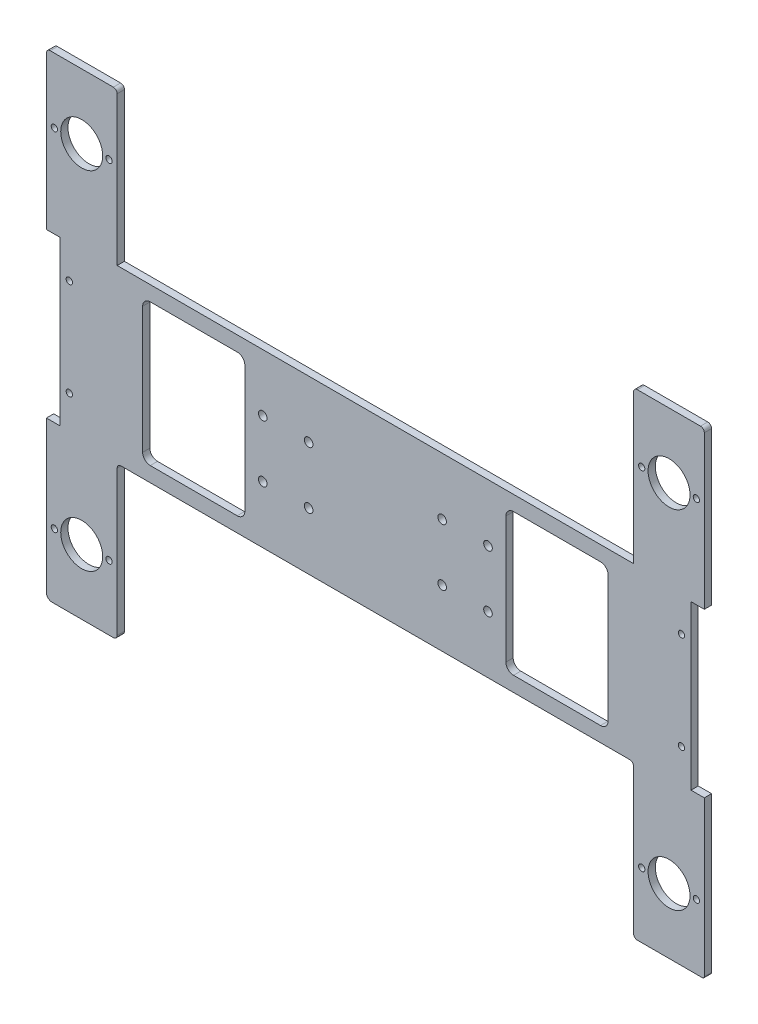
SolidWorks part; units mm, degrees
ref_plane "Front Plane" through (0, 0, 0) normal (0, 0, 1) x (1, 0, 0)
ref_plane "Top Plane" through (0, 0, 0) normal (0, 1, 0) x (1, 0, 0)
ref_plane "Right Plane" through (0, 0, 0) normal (1, 0, 0) x (0, 0, -1)
ref_plane "Plane1" through (0, 150, 0) normal (0, 1, 0) x (1, 0, 0)
ref_plane "Plane2" through (0, -150, 0) normal (0, 1, 0) x (1, 0, 0)
ref_plane "Plane3" through (150, 0, 0) normal (1, 0, 0) x (0, 0, -1)
ref_plane "Plane4" through (-150, 0, 0) normal (1, 0, 0) x (0, 0, -1)
sketch "Sketch2" plane through (0, 0, 0) normal (0, 0, 1) x (1, 0, 0)
  line L0 (0, -10.2) -> (0, 50.0764) construction
  line L5 (-59.06, 39.945) -> (-59.06, 10.055) construction
  line L23 (-170.5, 150) -> (-137.4, 150)
  line L24 (139.6652, 116) -> (168.3348, 116) construction
  line L30 (-172.5, 148) -> (-172.5, 67.8042)
  line L31 (-169.5, -100) -> (-137.4, -100)
  line L39 (172.5, 148) -> (172.5, 67.8042)
  line L40 (-152.1866, -81.0661) -> (-123.5266, -81.0661) construction
  line L42 (-135.4, 148) -> (-135.4, 70)
  line L43 (-135.4, 70) -> (135.4, 70)
  line L44 (135.4, 148) -> (135.4, 70)
  line L45 (137.4, 150) -> (170.5, 150)
  line L47 (-72.4574, 62.1714) -> (-118.0552, 62.1714)
  line L48 (72.4574, 62.1714) -> (118.0552, 62.1714)
  line L49 (68.4574, 58.1714) -> (68.4574, -8.1714)
  line L50 (72.4574, -12.1714) -> (118.0552, -12.1714)
  line L51 (122.0552, 58.1714) -> (122.0552, -8.1714)
  line L52 (68.4574, 62.1714) -> (122.0552, -12.1714) construction
  line L53 (68.4574, -12.1714) -> (122.0552, 62.1714) construction
  line L54 (-68.4574, 58.1714) -> (-68.4574, -8.1714)
  line L55 (-72.4574, -12.1714) -> (-118.0552, -12.1714)
  line L56 (-122.0552, 58.1714) -> (-122.0552, -8.1714)
  line L57 (177.1787, -66.0847) -> (177.1787, 11.9153) construction
  line L61 (165.5, 67.8042) -> (165.5, -17.8042)
  line L62 (165.5, -17.8042) -> (172.5, -17.8042)
  line L63 (172.5, 67.8042) -> (165.5, 67.8042)
  line L65 (172.5, -17.8042) -> (172.5, -99)
  line L66 (177.1787, 0) -> (1253.7576, 0) construction
  line L67 (-165.5, 67.8042) -> (-165.5, -17.8042)
  line L69 (-172.5, -17.8042) -> (-172.5, -97)
  line L70 (-160.5, 50.5) -> (-160.5, -0.5) construction
  line L71 (-172.5, 67.8042) -> (-165.5, 67.8042)
  line L72 (-172.5, -17.8042) -> (-165.5, -17.8042)
  line L74 (162.5, 25) -> (139.6652, 25) construction
  line L75 (-135.4, -98) -> (-135.4, -22)
  line L76 (-133.4, -20) -> (133.4, -20)
  line L77 (135.4, -22) -> (135.4, -98)
  line L78 (137.4, -100) -> (171.5, -100)
  circle A1 centre (-168.3348, 116) radius 1.65
  circle A2 centre (-139.6652, 116) radius 1.65
  circle A3 centre (168.3348, 116) radius 1.65
  circle A4 centre (139.6652, 116) radius 1.65
  circle A9 centre (154, 116) radius 11
  circle A10 centre (-154, 116) radius 11
  circle A17 centre (160.5, -0.5) radius 1.65
  circle A18 centre (160.5, 50.5) radius 1.65
  circle A19 centre (-160.5, -0.5) radius 1.65
  circle A20 centre (-160.5, 50.5) radius 1.65
  circle A27 centre (-35, 10.055) radius 2.25
  circle A32 centre (-35, 39.945) radius 2.25
  circle A33 centre (-59.06, 39.945) radius 2.25
  circle A34 centre (-59.06, 10.055) radius 2.25
  circle A35 centre (59.06, 10.055) radius 2.25
  circle A36 centre (35, 10.055) radius 2.25
  circle A37 centre (35, 39.945) radius 2.25
  circle A38 centre (59.06, 39.945) radius 2.25
  arc A42 (-170.5, 150) -> (-172.5, 148) centre (-170.5, 148) ccw
  arc A43 (170.5, 150) -> (172.5, 148) centre (170.5, 148) cw
  arc A45 (-172.5, -97) -> (-169.5, -100) centre (-169.5, -97) ccw
  arc A46 (135.4, 148) -> (137.4, 150) centre (137.4, 148) cw
  arc A47 (-135.4, 148) -> (-137.4, 150) centre (-137.4, 148) ccw
  arc A48 (68.4574, -8.1714) -> (72.4574, -12.1714) centre (72.4574, -8.1714) ccw
  arc A49 (118.0552, -12.1714) -> (122.0552, -8.1714) centre (118.0552, -8.1714) ccw
  arc A50 (118.0552, 62.1714) -> (122.0552, 58.1714) centre (118.0552, 58.1714) cw
  arc A51 (72.4574, 62.1714) -> (68.4574, 58.1714) centre (72.4574, 58.1714) ccw
  arc A52 (-118.0552, 62.1714) -> (-122.0552, 58.1714) centre (-118.0552, 58.1714) ccw
  arc A53 (-72.4574, 62.1714) -> (-68.4574, 58.1714) centre (-72.4574, 58.1714) cw
  arc A54 (-68.4574, -8.1714) -> (-72.4574, -12.1714) centre (-72.4574, -8.1714) cw
  arc A55 (-118.0552, -12.1714) -> (-122.0552, -8.1714) centre (-118.0552, -8.1714) cw
  arc A64 (172.5, -99) -> (171.5, -100) centre (171.5, -99) cw
  circle A68 centre (168.3348, -66) radius 1.65
  circle A69 centre (139.6652, -66) radius 1.65
  circle A70 centre (154, -66) radius 11
  circle A71 centre (-154, -66) radius 11
  circle A72 centre (-139.6652, -66) radius 1.65
  circle A73 centre (-168.3348, -66) radius 1.65
  arc A74 (135.4, -98) -> (137.4, -100) centre (137.4, -98) ccw
  arc A75 (133.4, -20) -> (135.4, -22) centre (133.4, -22) cw
  arc A76 (-135.4, -22) -> (-133.4, -20) centre (-133.4, -22) cw
  arc A77 (-135.4, -98) -> (-137.4, -100) centre (-137.4, -98) cw
  point P0 (0, 0)
  point P2 (0, 0)
  point P4 (0, 150)
  point P11 (-160.5, 25)
  point P12 (95.2563, 25)
  point P23 (-59.06, 25)
  point P24 (135.4, -100)
  point P39 (-165.5, 25)
  point P45 (135.4, 150)
  point P82 (177.1787, -27.0847)
  point P111 (-122.0552, 25)
  point P132 (-68.4574, 25)
  dimension "D3" = 51
  dimension "D7" = 34
  dimension "D8" = 3.3
  dimension "D9" = 18.5
  dimension "D10" = 22
  dimension "D11" = 74.3428
  dimension "D12" = 135.4
  dimension "D13" = 53.5977
  dimension "D16" = 68.4574
  dimension "D18" = 2
  dimension "D19" = 3.3
  dimension "D6" = 14.3348
  dimension "D20" = 14.3348
  dimension "D21" = 2
  dimension "D23" = 4.5
  dimension "D25" = 4.5
  dimension "D26" = 4.5
  dimension "D27" = 29.89
  dimension "D29" = 24.06
  dimension "D31" = 4
  dimension "D32" = 7
  dimension "D33" = 1
  dimension "D34" = 135.4
  dimension "D35" = 85.6084
  dimension "D36" = 80
  dimension "D37" = 80
  dimension "D4" = 3.3
  dimension "D5" = 5
  dimension "D22" = 29.89
  dimension "D28" = 24.06
  dimension "D30" = 35
  dimension "D15" = 2
  dimension "D14" = 45
extrude "Boss-Extrude1" add sketch "Sketch2" along normal blind 3.8
